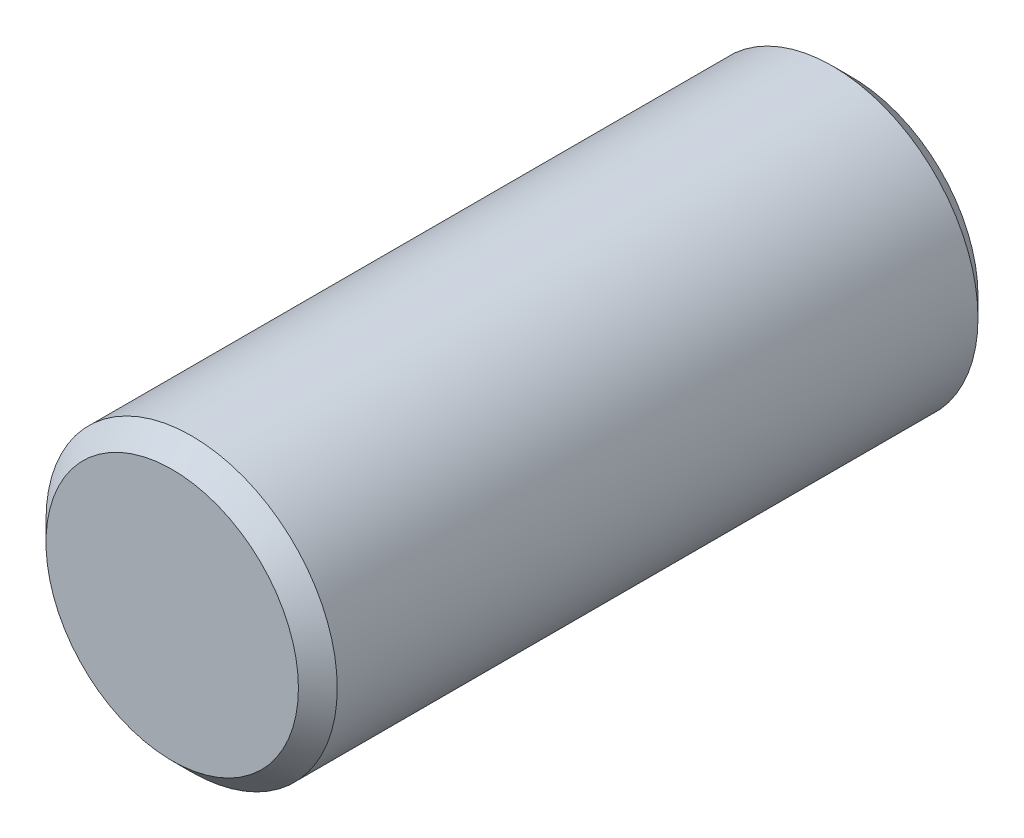
SolidWorks part; units mm, degrees
ref_plane "Front Plane" through (0, 0, 0) normal (0, 0, 1) x (1, 0, 0)
ref_plane "Top Plane" through (0, 0, 0) normal (0, 1, 0) x (1, 0, 0)
ref_plane "Right Plane" through (0, 0, 0) normal (1, 0, 0) x (0, 0, -1)
sketch "Sketch1" plane through (0, 0, 0) normal (0, 0, 1) x (1, 0, 0)
  circle A0 centre (0, 0) radius 1.5
  dimension "D1" = 3
extrude "Boss-Extrude1" add sketch "Sketch1" along normal mid plane 7
chamfer "Chamfer1" distance 0.2 angle 45 2 edges at (1.5, 0, -3.5) (1.5, 0, 3.5)
